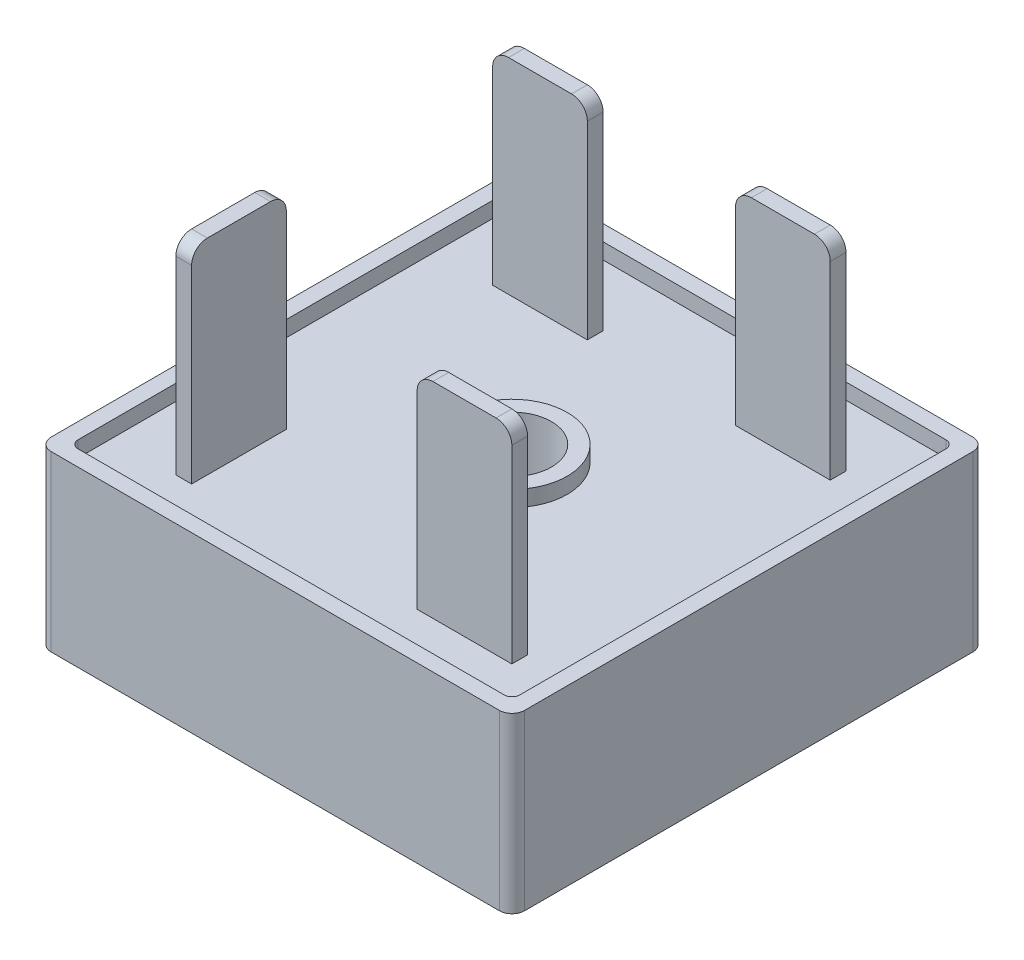
SolidWorks part; units mm, degrees
material "6061 Alloy"
ref_plane "Front Plane" through (0, 0, 0) normal (0, 0, 1) x (1, 0, 0)
ref_plane "Top Plane" through (0, 0, 0) normal (0, 1, 0) x (1, 0, 0)
ref_plane "Right Plane" through (0, 0, 0) normal (1, 0, 0) x (0, 0, -1)
sketch "Sketch1" plane through (0, 0, 0) normal (0, 1, 0) x (1, 0, 0)
  line L0 (-7.8818, 18.2554) -> (-7.8818, -11.7446) construction
  line L1 (-22.0818, 18.2554) -> (6.3182, 18.2554)
  line L2 (-22.8818, 17.4554) -> (-22.8818, -10.9446)
  line L3 (-22.0818, -11.7446) -> (6.3182, -11.7446)
  line L4 (7.1182, 17.4554) -> (7.1182, -10.9446)
  line L5 (-22.8818, 18.2554) -> (7.1182, -11.7446) construction
  line L6 (7.1182, 18.2554) -> (-22.8818, -11.7446) construction
  circle A0 centre (-7.8818, 3.2554) radius 2.5
  arc A1 (6.3182, -11.7446) -> (7.1182, -10.9446) centre (6.3182, -10.9446) ccw
  arc A2 (-22.8818, -10.9446) -> (-22.0818, -11.7446) centre (-22.0818, -10.9446) ccw
  arc A3 (6.3182, 18.2554) -> (7.1182, 17.4554) centre (6.3182, 17.4554) cw
  arc A4 (-22.0818, 18.2554) -> (-22.8818, 17.4554) centre (-22.0818, 17.4554) ccw
  dimension "D3" = 5
  dimension "D4" = 0.8
  dimension "D1" = 30
  dimension "D2" = 30
extrude "Boss-Extrude1" add sketch "Sketch1" along normal blind 11
sketch "Sketch2" plane through (0, 11, 0) normal (0, 1, 0) x (1, 0, 0)
  line L0 (-22.8818, 18.2554) -> (7.1182, -11.7446) construction
  line L1 (-21.3818, 17.2554) -> (5.6182, 17.2554)
  line L2 (-21.8818, 16.7554) -> (-21.8818, -10.2446)
  line L3 (-21.3818, -10.7446) -> (5.6182, -10.7446)
  line L4 (6.1182, 16.7554) -> (6.1182, -10.2446)
  line L5 (-22.8818, 17.4554) -> (-22.8818, -10.9446) construction
  line L6 (-22.0818, 18.2554) -> (6.3182, 18.2554) construction
  line L7 (-22.0818, -11.7446) -> (6.3182, -11.7446) construction
  circle A0 centre (-7.8818, 3.2554) radius 3.5
  arc A1 (5.6182, -10.7446) -> (6.1182, -10.2446) centre (5.6182, -10.2446) ccw
  arc A2 (-21.8818, -10.2446) -> (-21.3818, -10.7446) centre (-21.3818, -10.2446) ccw
  arc A3 (5.6182, 17.2554) -> (6.1182, 16.7554) centre (5.6182, 16.7554) cw
  arc A4 (-21.3818, 17.2554) -> (-21.8818, 16.7554) centre (-21.3818, 16.7554) ccw
  point P17 (6.1182, -10.7446)
  point P24 (-21.8818, 17.2554)
  dimension "D4" = 7
  dimension "D5" = 0.5
  dimension "D1" = 1
  dimension "D2" = 1
  dimension "D3" = 1
extrude "Cut-Extrude1" cut sketch "Sketch2" against normal blind 1
sketch "Sketch3" plane through (0, 10, 0) normal (0, 1, 0) x (1, 0, 0)
  line L1 (-18.224, 13.3722) -> (-12.224, 13.3722)
  line L2 (-18.224, 13.3722) -> (-18.224, 12.3722)
  line L3 (-18.224, 12.3722) -> (-12.224, 12.3722)
  line L4 (-12.224, 13.3722) -> (-12.224, 12.3722)
  line L5 (-2.8322, 13.3722) -> (3.1678, 13.3722)
  line L6 (-2.8322, 13.3722) -> (-2.8322, 12.3722)
  line L7 (-2.8322, 12.3722) -> (3.1678, 12.3722)
  line L8 (3.1678, 13.3722) -> (3.1678, 12.3722)
  line L9 (-2.8322, -7.8045) -> (3.1678, -7.8045)
  line L10 (-2.8322, -7.8045) -> (-2.8322, -6.8045)
  line L11 (-2.8322, -6.8045) -> (3.1678, -6.8045)
  line L12 (3.1678, -7.8045) -> (3.1678, -6.8045)
  line L13 (-17.8533, -2.0745) -> (-16.8533, -2.0745)
  line L14 (-17.8533, -2.0745) -> (-17.8533, -8.0745)
  line L15 (-17.8533, -8.0745) -> (-16.8533, -8.0745)
  line L16 (-16.8533, -2.0745) -> (-16.8533, -8.0745)
  dimension "D1" = 1
  dimension "D2" = 6
  dimension "D3" = 6
  dimension "D4" = 1
  dimension "D5" = 6
  dimension "D6" = 1
  dimension "D7" = 1
  dimension "D8" = 6
extrude "Boss-Extrude2" add sketch "Sketch3" along normal blind 13
fillet "Fillet1" radius 1 8 edges at (-18.224, 23, -12.8722) (-12.224, 23, -12.8722) (3.1678, 23, -12.8722) (-2.8322, 23, -12.8722) (-17.3533, 23, 2.0745) (-17.3533, 23, 8.0745) (-2.8322, 23, 7.3045) (3.1678, 23, 7.3045)
